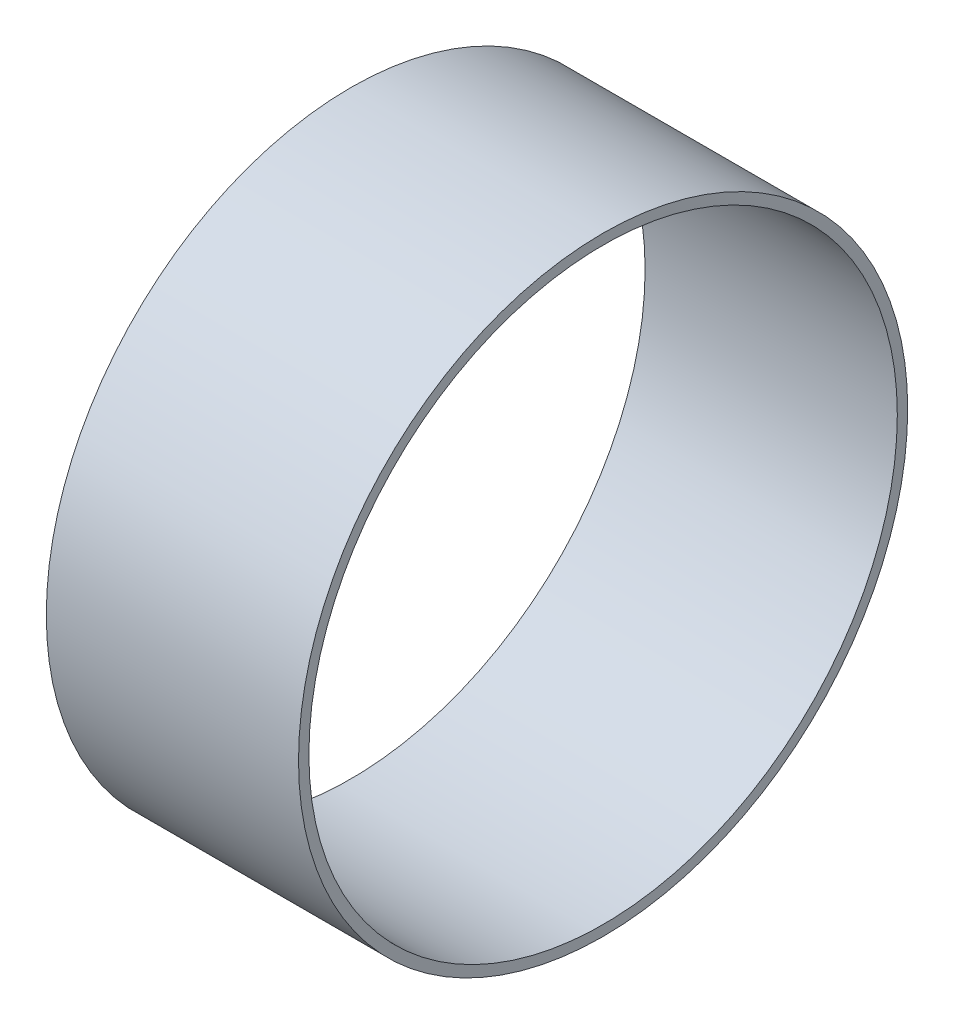
SolidWorks part; units mm, degrees
ref_plane "Front Plane" through (0, 0, 0) normal (0, 0, 1) x (1, 0, 0)
ref_plane "Top Plane" through (0, 0, 0) normal (0, 1, 0) x (1, 0, 0)
ref_plane "Right Plane" through (0, 0, 0) normal (1, 0, 0) x (0, 0, -1)
sketch "Sketch1" plane through (0, 0, 0) normal (0, 1, 0) x (1, 0, 0)
  line L0 (-80.6125, 29) -> (-80.6125, -29) construction
  line L1 (-80.6125, 23.2938) -> (-99.9, 23.2938)
  line L2 (-80.6125, 23.2938) -> (-80.6125, 22.5)
  line L3 (-80.6125, 22.5) -> (-99.9, 22.5)
  line L4 (-99.9, 23.2938) -> (-99.9, 22.5)
  point P4 (-99.5582, 23.5087)
  point P5 (-99.9, 23.5124)
  point P6 (-99.9, 22.5)
  point P8 (-80.6125, 25.7688)
  dimension "D1" = 0.7937
ref_axis "Axis1" through (-79.6481, 0, 0) along (-1, 0, 0)
revolve "Revolve1" add sketch "Sketch1" angle 360 about axis through (-79.6481, 0, 0) along (-1, 0, 0)
